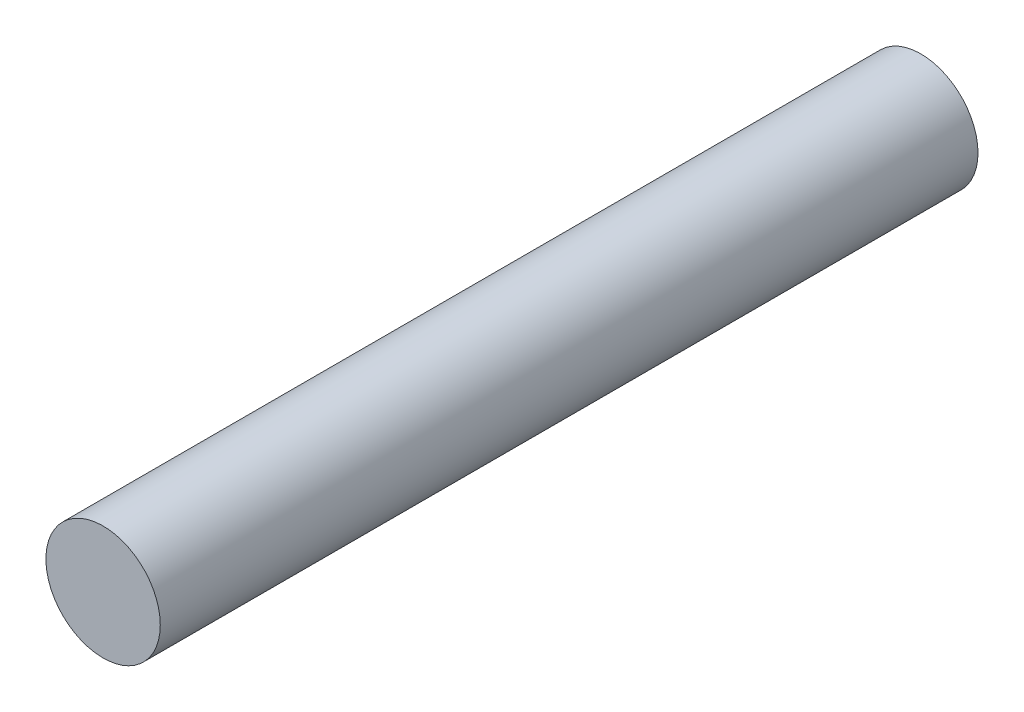
SolidWorks part; units mm, degrees
ref_plane "Front Plane" through (0, 0, 0) normal (0, 0, 1) x (1, 0, 0)
ref_plane "Top Plane" through (0, 0, 0) normal (0, 1, 0) x (1, 0, 0)
ref_plane "Right Plane" through (0, 0, 0) normal (1, 0, 0) x (0, 0, -1)
sketch "Sketch1" plane through (0, 0, 0) normal (0, 0, 1) x (1, 0, 0)
  circle A0 centre (0, 0) radius 3.175
  dimension "D1" = 6.35
extrude "Boss-Extrude1" add sketch "Sketch1" along normal blind 45.3946
